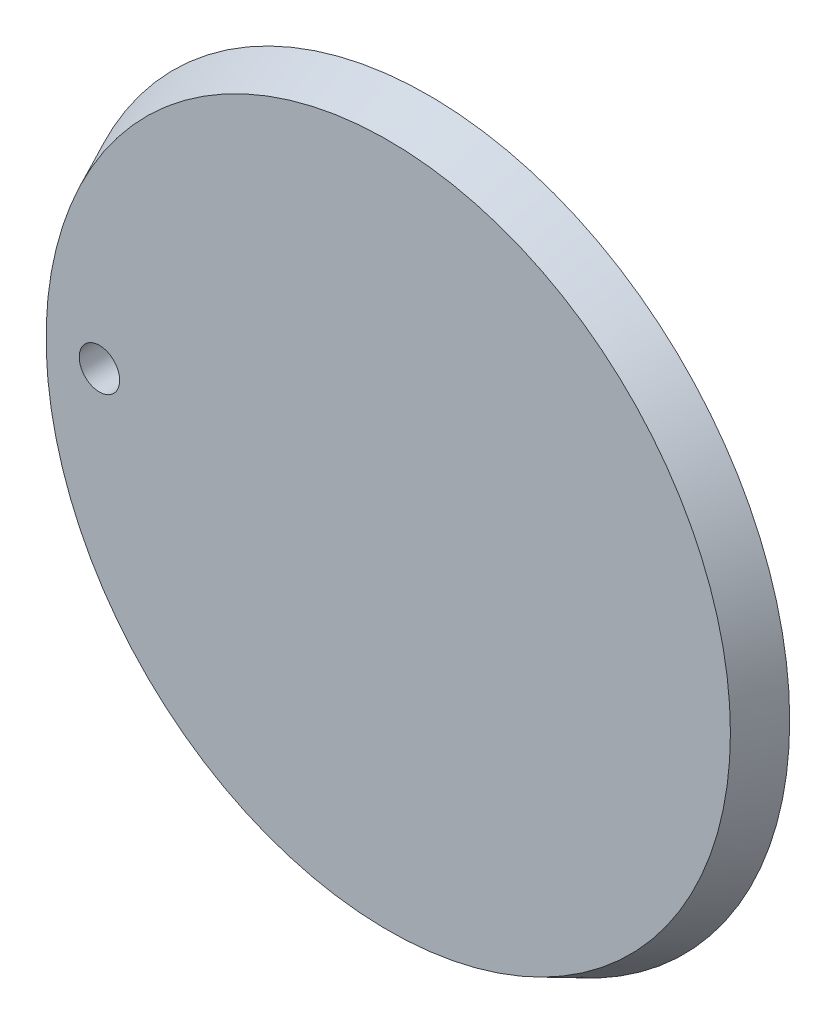
SolidWorks part; units mm, degrees
ref_plane "Front Plane" through (0, 0, 0) normal (0, 0, 1) x (1, 0, 0)
ref_plane "Top Plane" through (0, 0, 0) normal (0, 1, 0) x (1, 0, 0)
ref_plane "Right Plane" through (0, 0, 0) normal (1, 0, 0) x (0, 0, -1)
sketch "Sketch2" plane through (0, 0, 0) normal (0, 0, 1) x (1, 0, 0)
  circle A0 centre (0, 0) radius 25
  dimension "D1" = 50
extrude "Boss-Extrude2" add sketch "Sketch2" along normal blind 10 and the other way blind 14
sketch "Sketch4" plane through (0, 0, 10) normal (0, 0, 1) x (1, 0, 0)
  circle A0 centre (0, 0) radius 62.5
  dimension "D1" = 125
extrude "Boss-Extrude3" add sketch "Sketch4" along normal blind 7 draft 25
sketch "Sketch6" plane through (0, 0, 17) normal (0, 0, 1) x (1, 0, 0)
  circle A0 centre (-50, 0) radius 3.5
  dimension "D1" = 7
  dimension "D2" = 50
extrude "Cut-Extrude2" cut sketch "Sketch6" against normal blind 5
